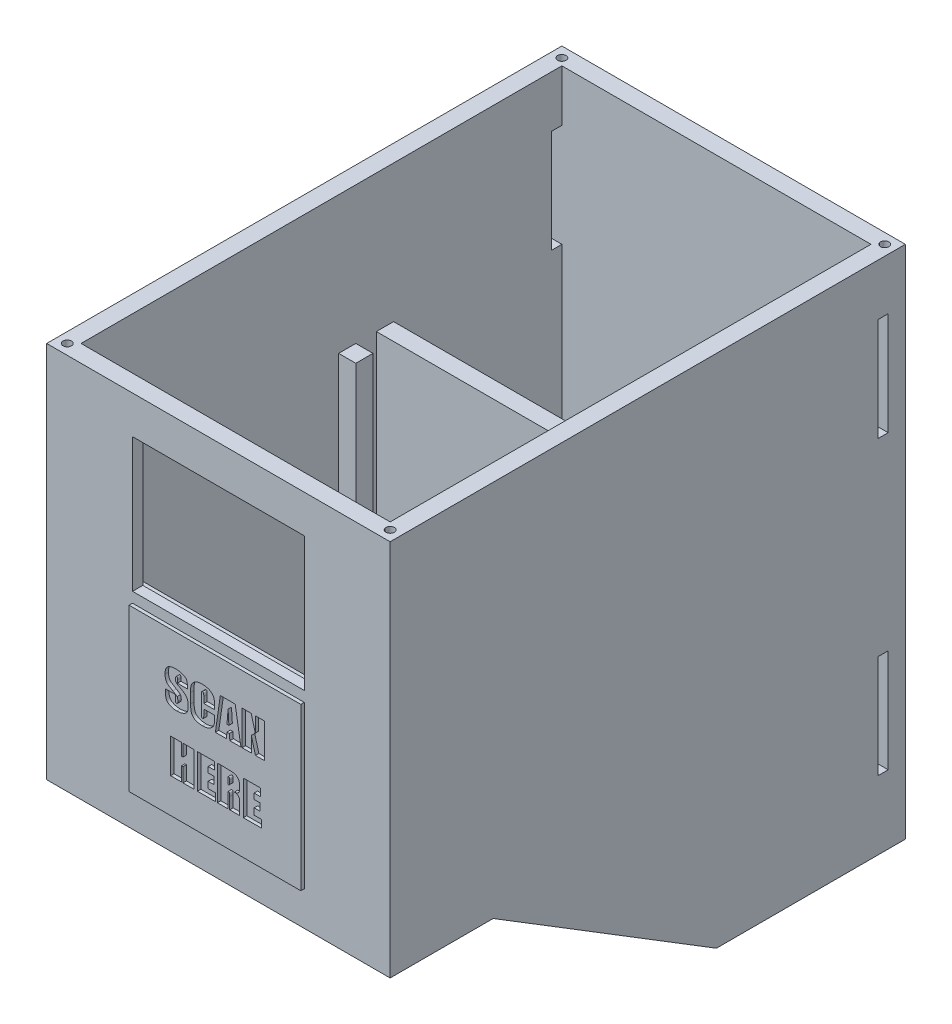
SolidWorks part; units mm, degrees
ref_plane "Front Plane" through (0, 0, 0) normal (0, 0, 1) x (1, 0, 0)
ref_plane "Top Plane" through (0, 0, 0) normal (0, 1, 0) x (1, 0, 0)
ref_plane "Right Plane" through (0, 0, 0) normal (1, 0, 0) x (0, 0, -1)
sketch "Sketch1" plane through (0, 0, 0) normal (0, 1, 0) x (1, 0, 0)
  line L1 (-50, -75) -> (50, -75)
  line L2 (-50, -75) -> (-50, 75)
  line L3 (-50, 75) -> (50, 75)
  line L4 (50, -75) -> (50, 75)
  line L5 (-50, -75) -> (50, 75) construction
  line L6 (-50, 75) -> (50, -75) construction
  point P0 (0, 0)
  dimension "D1" = 100
  dimension "D2" = 150
extrude "Boss-Extrude1" add sketch "Sketch1" along normal blind 150
sketch "Sketch13" plane through (50, 0, 0) normal (1, 0, 0) x (0, 0, -1)
  line L0 (-45, 40) -> (20, 0)
  line L1 (-75, 0) -> (-45, 0)
  line L2 (-75, 0) -> (-75, 40)
  line L3 (-75, 40) -> (-45, 40)
  line L5 (-75, 0) -> (75, 0) construction
  line L8 (-45, 0) -> (20, 0)
  dimension "D1" = 30
  dimension "D2" = 40
  dimension "D3" = 55
extrude "Cut-Extrude7" cut sketch "Sketch13" against normal up to next
shell "Shell1" thickness 5
sketch "Sketch3" plane through (0, 0, 0) normal (0, -1, 0) x (1, 0, 0)
  line L1 (50, 45) -> (50, 75) construction
  circle A0 centre (0, 60) radius 4
  circle A1 centre (-5, 50) radius 1.5
  circle A2 centre (5, 50) radius 1.5
  dimension "D3" = 8
  dimension "D4" = 3
  dimension "D5" = 10
  dimension "D7" = 10
  dimension "D8" = 5
  dimension "D1" = 60
  dimension "D2" = 50
extrude "Cut-Extrude2" cut sketch "Sketch3" against normal up to next
sketch "Sketch5" plane through (0, 0, 75) normal (0, 0, 1) x (1, 0, 0)
  line L0 (50, 150) -> (50, 40) construction
  line L1 (-25, 50) -> (25, 50)
  line L2 (-25, 50) -> (-25, 97)
  line L3 (-25, 97) -> (25, 97)
  line L4 (25, 50) -> (25, 97)
  line L5 (-25, 50) -> (25, 97) construction
  line L6 (-25, 97) -> (25, 50) construction
  line L7 (-50, 150) -> (50, 150) construction
  point P0 (0, 73.5)
  dimension "D1" = 50
  dimension "D2" = 47
  dimension "D3" = 50
  dimension "D4" = 76.5
extrude "Boss-Extrude3" add sketch "Sketch5" along normal blind 1
sketch "Sketch8" plane through (0, 0, 75) normal (0, 0, 1) x (1, 0, 0)
  line L0 (-50, 150) -> (-50, 40) construction
  line L1 (-25, 100) -> (25, 100)
  line L2 (-25, 100) -> (-25, 139)
  line L3 (-25, 139) -> (25, 139)
  line L4 (25, 100) -> (25, 139)
  line L5 (-25, 100) -> (25, 139) construction
  line L6 (-25, 139) -> (25, 100) construction
  line L7 (-50, 150) -> (50, 150) construction
  point P0 (0, 119.5)
  dimension "D1" = 50
  dimension "D2" = 39
  dimension "D3" = 50
  dimension "D4" = 50
extrude "Cut-Extrude3" cut sketch "Sketch8" against normal up to next
sketch "Sketch18" plane through (0, 0, 70) normal (0, 0, -1) x (-1, 0, 0)
  line L0 (-25, 139) -> (25, 139) construction
  line L1 (30, 99) -> (-26, 99)
  line L2 (30, 99) -> (30, 140)
  line L3 (30, 140) -> (-26, 140)
  line L4 (-26, 99) -> (-26, 140)
  line L6 (-25, 100) -> (-25, 139) construction
  line L7 (25, 139) -> (25, 100) construction
  dimension "D1" = 1
  dimension "D2" = 41
  dimension "D3" = 1
  dimension "D4" = 5
extrude "Cut-Extrude9" cut sketch "Sketch18" against normal blind 2
sketch "Sketch20" plane through (0, 0, 76) normal (0, 0, 1) x (1, 0, 0)
  line L0 (25, 97) -> (-25, 97) construction
  line L1 (-23, 96) -> (23, 96)
  line L2 (-23, 96) -> (-23, 51)
  line L3 (-23, 51) -> (23, 51)
  line L4 (23, 96) -> (23, 51)
  line L5 (-25, 50) -> (25, 50) construction
  line L6 (25, 50) -> (25, 97) construction
  line L7 (-25, 97) -> (-25, 50) construction
  dimension "D1" = 1
  dimension "D2" = 1
  dimension "D3" = 2
  dimension "D4" = 2
extrude "Cut-Extrude10" cut sketch "Sketch20" against normal blind 15 from offset 4 offset against normal yes
sketch "Sketch21" plane through (0, 45, 0) normal (0, 1, 0) x (1, 0, 0)
  line L1 (9, -52.5) -> (-9, -52.5)
  line L2 (9, -52.5) -> (9, -37.5)
  line L3 (9, -37.5) -> (-9, -37.5)
  line L4 (-9, -52.5) -> (-9, -37.5)
  circle A0 centre (5, -50) radius 1.5 construction
  circle A1 centre (-5, -50) radius 1.5 construction
  dimension "D3" = 4
  dimension "D1" = 4
  dimension "D2" = 2.5
  dimension "D4" = 15
extrude "Cut-Extrude11" cut sketch "Sketch21" against normal blind 2.5
sketch "Sketch22" plane through (-45, 0, 0) normal (1, 0, 0) x (0, 0, -1)
  line L0 (70, 150) -> (-70, 150) construction
  line L5 (70, 150) -> (70, 5) construction
  line L7 (-43.5848, 45) -> (21.4152, 5) construction
  line L8 (10, 150) -> (10, 12.0247)
  line L11 (10, 150) -> (5, 150)
  line L14 (5, 150) -> (5, 15.1017)
  line L15 (5, 15.1017) -> (10, 12.0247)
  dimension "D1" = 60
  dimension "D3" = 5
extrude "Boss-Extrude6" add sketch "Sketch22" along normal blind 5
mirror "Mirror2" about plane through (0, 0, 0) normal (1, 0, 0) of "Boss-Extrude6"
sketch "Sketch23" plane through (-45, 0, 0) normal (1, 0, 0) x (0, 0, -1)
  line L0 (16, 150) -> (21, 150)
  line L1 (70, 150) -> (10, 150) construction
  line L3 (21, 150) -> (21, 5.2555)
  line L4 (21, 5.2555) -> (16, 8.3324)
  line L6 (10, 12.0247) -> (10, 150) construction
  line L7 (16, 150) -> (16, 8.3324)
  line L8 (10, 12.0247) -> (21.4152, 5) construction
  dimension "D1" = 6
  dimension "D2" = 5
extrude "Boss-Extrude7" add sketch "Sketch23" along normal up to next
sketch "Sketch24" plane through (-45, 0, 0) normal (1, 0, 0) x (0, 0, -1)
  line L0 (70, 150) -> (70, 5) construction
  line L1 (70, 135) -> (67, 135)
  line L2 (70, 135) -> (70, 105)
  line L3 (70, 105) -> (67, 105)
  line L4 (67, 135) -> (67, 105)
  line L5 (70, 150) -> (21, 150) construction
  line L6 (70, 5) -> (21.4152, 5) construction
  line L7 (70, 20) -> (67, 20)
  line L8 (70, 20) -> (70, 50)
  line L9 (70, 50) -> (67, 50)
  line L10 (67, 20) -> (67, 50)
  dimension "D1" = 15
  dimension "D2" = 30
  dimension "D3" = 3
  dimension "D4" = 15
extrude "Cut-Extrude12" cut sketch "Sketch24" against normal through all both and the other way through all
sketch "Sketch28" plane through (0, 0, 76) normal (0, 0, 1) x (1, 0, 0)
  line L0 (-25, 73.5) -> (25, 73.5) construction
  line L1 (-25, 97) -> (-25, 50) construction
  line L2 (25, 50) -> (25, 97) construction
  line L3 (-25, 77.511) -> (25, 77.511) construction
  text T0 "SCAN\r\nHERE" font "Impact" height 10
extrude "Cut-Extrude14" cut sketch "Sketch28" against normal blind 1
sketch "Sketch30" plane through (0, 0, -75) normal (0, 0, -1) x (-1, 0, 0)
  text T0 "IBE VAN DE VEIRE\r\nSTEF GIELEN" font "Comic Sans MS" height 5
extrude "Cut-Extrude16" cut sketch "Sketch30" against normal blind 1
sketch "Sketch32" plane through (0, 150, 0) normal (0, 1, 0) x (1, 0, 0)
  line L0 (-50, 75) -> (-50, -75) construction
  line L1 (50, 75) -> (-50, 75) construction
  line L2 (-50, -75) -> (50, -75) construction
  line L3 (50, -75) -> (50, 75) construction
  circle A0 centre (-47, 72) radius 1.225
  circle A1 centre (-47, -72) radius 1.225
  circle A2 centre (47, -72) radius 1.225
  circle A3 centre (47, 72) radius 1.225
  dimension "D1" = 2.45
  dimension "D2" = 3
  dimension "D3" = 3
  dimension "D4" = 2.45
  dimension "D5" = 3
  dimension "D6" = 3
  dimension "D7" = 2.45
  dimension "D8" = 3
  dimension "D9" = 3
  dimension "D10" = 2.45
  dimension "D11" = 3
  dimension "D12" = 3
extrude "Cut-Extrude17" cut sketch "Sketch32" against normal blind 20
sketch "Sketch33" plane through (0, 150, 0) normal (0, 1, 0) x (1, 0, 0)
  line L1 (-45, 5) -> (45, 5)
  line L2 (-45, 5) -> (-45, 21)
  line L3 (-45, 21) -> (45, 21)
  line L4 (45, 5) -> (45, 21)
extrude "Cut-Extrude18" cut sketch "Sketch33" against normal blind 40
